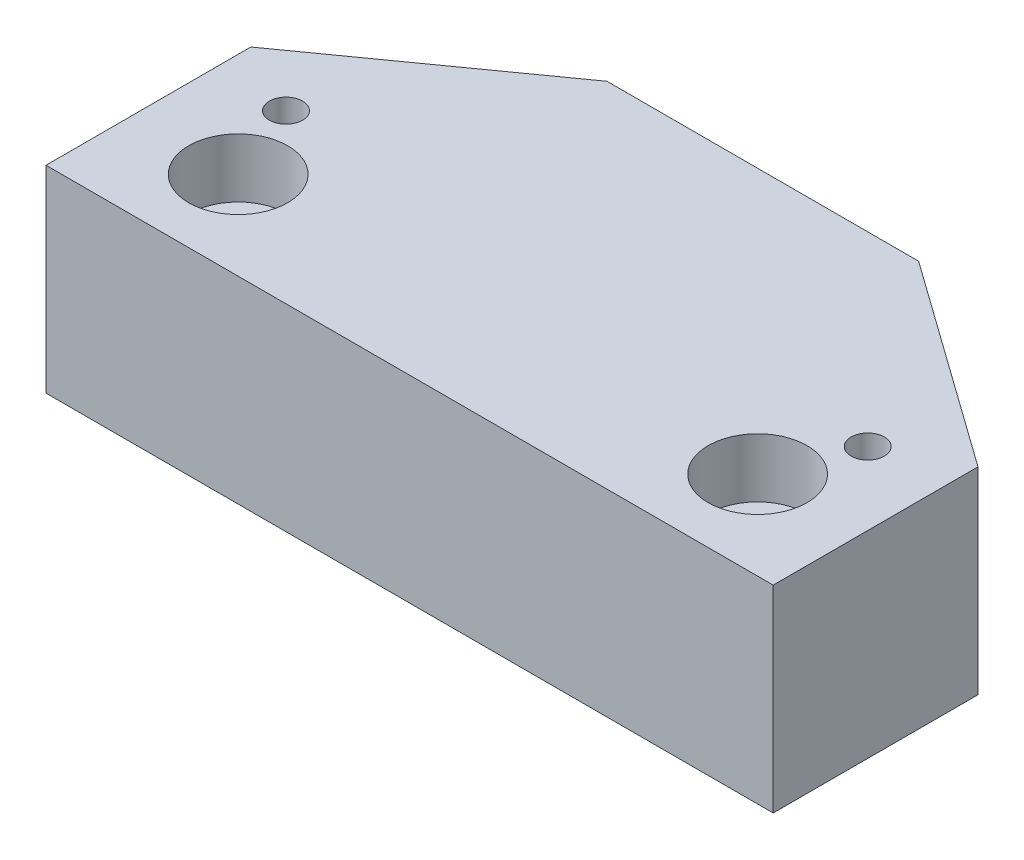
SolidWorks part; units mm, degrees
ref_plane "Front Plane" through (0, 0, 0) normal (0, 0, 1) x (1, 0, 0)
ref_plane "Top Plane" through (0, 0, 0) normal (0, 1, 0) x (1, 0, 0)
ref_plane "Right Plane" through (0, 0, 0) normal (1, 0, 0) x (0, 0, -1)
sketch "Sketch1" plane through (0, 0, 0) normal (0, 1, 0) x (1, 0, 0)
  line L3 (0, 0) -> (-35, 0)
  line L4 (0, 0) -> (0, -17)
  line L5 (0, -17) -> (-35, -17)
  line L6 (-35, 0) -> (-35, -17)
  dimension "D8" = 35
  dimension "D9" = 17
extrude "Boss-Extrude1" add sketch "Sketch1" along normal blind 9.5
sketch "Sketch9" plane through (0, 0, 0) normal (0, -1, 0) x (1, 0, 0)
  line L0 (-35, 17) -> (0, 17) construction
  line L1 (-20.75, 12.75) -> (-35, 12.75) construction
  line L2 (-35, 0) -> (-35, 17) construction
  line L3 (-14.25, 12.75) -> (0, 12.75) construction
  line L4 (0, 17) -> (0, 0) construction
  circle A0 centre (-20.75, 12.75) radius 0.25
  circle A1 centre (-14.25, 12.75) radius 0.25
  dimension "D1" = 0.5
  dimension "D2" = 0.5
  dimension "D3" = 6.5
  dimension "D4" = 4.25
extrude "Cut-Extrude4" cut sketch "Sketch9" against normal blind 6
sketch "Sketch14" plane through (0, 0, 0) normal (0, -1, 0) x (1, 0, 0)
  line L0 (-35, 17) -> (0, 17) construction
  circle A0 centre (-14.25, 15.75) radius 0.25
  circle A1 centre (-20.75, 15.75) radius 0.25
  dimension "D4" = 0.5
  dimension "D5" = 0.5
  dimension "D1" = 6.5
  dimension "D2" = 1.25
extrude "Cut-Extrude9" cut sketch "Sketch14" against normal blind 6
ref_plane "Plane1" through (0, 6, 0) normal (0, -1, 0) x (-1, 0, 0)
sketch "Sketch16" plane through (0, 0, 0) normal (0, 0, -1) x (-1, 0, 0)
  line L0 (3, 9.5) -> (3, 0) construction
  line L1 (0, 9.5) -> (35, 9.5) construction
  line L2 (0, 0) -> (35, 0) construction
  line L3 (0, 9.5) -> (0, 0) construction
  dimension "D1" = 3
sketch "Sketch15" plane through (0, 6, 0) normal (0, -1, 0) x (-1, 0, 0)
  line L0 (14.25, -15.75) -> (3, 0)
ref_plane "Plane2" through (-14.25, 6, 15.75) normal (0.5812, 0, -0.8137) x (-0.8137, 0, -0.5812)
sketch "Sketch17" plane through (-14.25, 6, 15.75) normal (0.5812, 0, -0.8137) x (-0.8137, 0, -0.5812)
  circle A0 centre (0, -0.25) radius 0.25
  dimension "D1" = 0.5
sweep "Cut-Sweep1" cut profiles "Sketch17" path "Sketch15"
sketch "Sketch18" plane through (0, 0, 0) normal (0, -1, 0) x (1, 0, 0)
  line L0 (-10, 0) -> (0, 7.1429)
  line L1 (0, 0) -> (-35, 0) construction
  line L2 (0, 17) -> (0, 0) construction
  line L3 (-14.25, 15.75) -> (-3, 0) construction
  line L4 (0, 7.1429) -> (0, 0)
  line L5 (0, 0) -> (-10, 0)
  dimension "D1" = 90
  dimension "D2" = 10
extrude "Cut-Extrude10" cut sketch "Sketch18" against normal through all
hole_wizard "#6-40 Tapped Hole5" positions "Sketch23" profile "Sketch22" tap size "#6-40" standard "ANSI Inch"
sketch "Sketch23" plane through (-3.3784, 0, 4.7297) normal (0.5812, 0, -0.8137) x (-0.8137, 0, -0.5812)
  point P0 (2.4412, 5.75)
sketch "Sketch22" plane through (-5.3649, 5.75, 3.3108) normal (0, 1, 0) x (-0.8137, 0, -0.5812)
  line L0 (0, 0) -> (0, 5.8623)
  line L1 (0, 5.8623) -> (1.4351, 5)
  line L2 (1.4351, 5) -> (1.4351, 0)
  line L5 (1.4351, 0) -> (0, 0)
  line L10 (0, 5.8623) -> (-1.4351, 5) construction
  line L11 (0, -6.35) -> (0, 107.95) construction
  dimension "Tap Drill Dia." = 2.8702
  dimension "Tap Drill Depth" = 5
  dimension "Drill Angle" = 118
cosmetic thread "Hole Thread3" parameters "D1"=5, "D2"=3.5052
ref_plane "Plane3" through (-17.5, 0, 0) normal (-1, 0, 0) x (0, 0, 1)
mirror "Mirror1" about plane through (-17.5, 0, 0) normal (-1, 0, 0) of "Cut-Sweep1", "Cut-Extrude10", "#6-40 Tapped Hole5"
sketch "Sketch26" plane through (0, 0, 0) normal (0, 0, -1) x (-1, 0, 0)
  line L0 (20.75, 0) -> (20.75, 9.5) construction
  line L1 (10, 0) -> (25, 0) construction
  line L2 (10, 9.5) -> (25, 9.5) construction
sketch "Sketch27" plane through (0, 6, 0) normal (0, -1, 0) x (1, 0, 0)
  line L0 (-20.75, 12.75) -> (-20.75, 0)
ref_plane "Plane4" through (-20.75, 6, 12.75) normal (0, 0, -1) x (-1, 0, 0)
sketch "Sketch28" plane through (-20.75, 6, 12.75) normal (0, 0, -1) x (-1, 0, 0)
  circle A0 centre (0, -0.25) radius 0.25
  dimension "D1" = 0.5
sweep "Cut-Sweep2" cut profiles "Sketch28" path "Sketch27"
hole_wizard "#6-40 Tapped Hole6" positions "Sketch30" profile "Sketch29" tap size "#6-40" standard "ANSI Inch"
sketch "Sketch30" plane through (0, 0, 0) normal (0, 0, -1) x (-1, 0, 0)
  point P0 (20.75, 5.75)
sketch "Sketch29" plane through (-20.75, 5.75, 0) normal (1, 0, 0) x (0, 1, 0)
  line L0 (0, 0) -> (0, 5.8623)
  line L1 (0, 5.8623) -> (1.4351, 5)
  line L2 (1.4351, 5) -> (1.4351, 0)
  line L5 (1.4351, 0) -> (0, 0)
  line L10 (0, 5.8623) -> (-1.4351, 5) construction
  line L11 (0, -6.35) -> (0, 107.95) construction
  dimension "Tap Drill Dia." = 2.8702
  dimension "Tap Drill Depth" = 5
  dimension "Drill Angle" = 118
cosmetic thread "Hole Thread4" parameters "D1"=5, "D2"=3.5052
mirror "Mirror2" about plane through (-17.5, 0, 0) normal (-1, 0, 0) of "Cut-Sweep2", "#6-40 Tapped Hole6"
sketch "Sketch31" plane through (0, 9.5, 0) normal (0, 1, 0) x (1, 0, 0)
  line L0 (-35, -17) -> (0, -17) construction
  line L1 (0, -17) -> (0, -7.1429) construction
  line L2 (-35, -7.1429) -> (-35, -17) construction
  circle A0 centre (-5, -12.75) radius 1.475
  circle A1 centre (-3.5, -8.95) radius 0.8
  circle A2 centre (-30, -12.75) radius 1.475
  circle A3 centre (-31.5, -8.95) radius 0.8
  dimension "D1" = 1.6
  dimension "D2" = 2.95
  dimension "D3" = 8.05
  dimension "D4" = 4.25
  dimension "D5" = 3.5
  dimension "D6" = 3.5
  dimension "D7" = 5
  dimension "D8" = 4.25
  dimension "D9" = 5
extrude "Cut-Extrude11" cut sketch "Sketch31" against normal through all
sketch "Sketch32" plane through (0, 9.5, 0) normal (0, 1, 0) x (1, 0, 0)
  circle A0 centre (-30, -12.75) radius 2.38
  circle A1 centre (-5, -12.75) radius 2.38
  dimension "D1" = 4.76
extrude "Cut-Extrude12" cut sketch "Sketch32" against normal blind 2.84
ref_plane "Plane5" through (-6.2846, 0, 8.7984) normal (-0.5812, 0, 0.8137) x (0.8137, 0, 0.5812)
